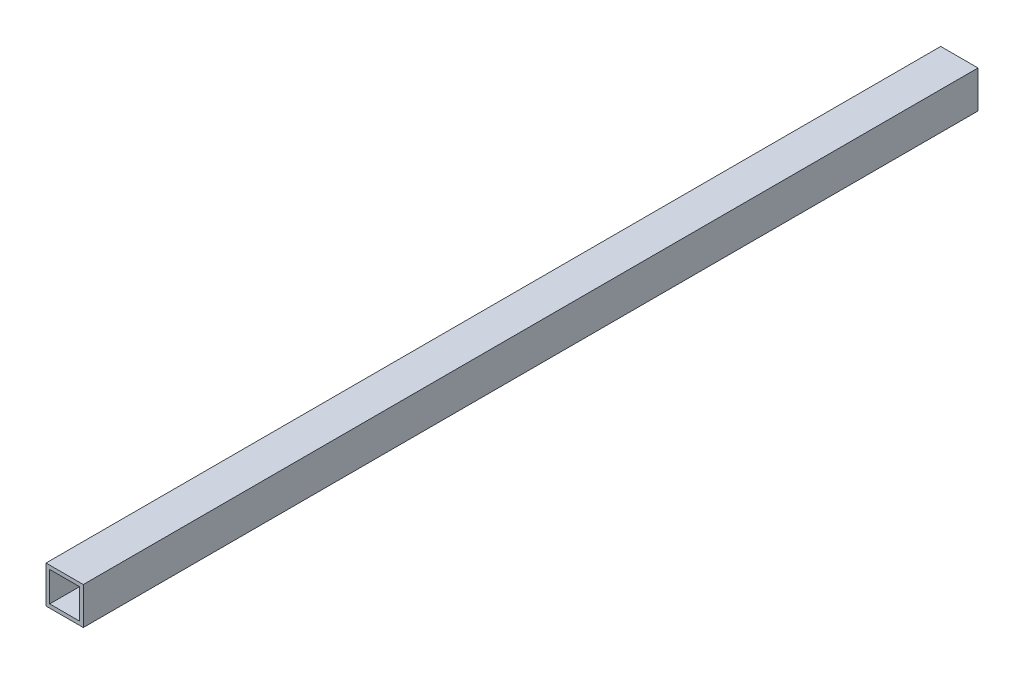
SolidWorks part; units mm, degrees
ref_plane "Płaszczyzna przednia" through (0, 0, 0) normal (0, 0, 1) x (1, 0, 0)
ref_plane "Płaszczyzna górna" through (0, 0, 0) normal (0, 1, 0) x (1, 0, 0)
ref_plane "Płaszczyzna prawa" through (0, 0, 0) normal (1, 0, 0) x (0, 0, -1)
sketch "Szkic1" plane through (0, 0, 0) normal (0, 0, 1) x (1, 0, 0)
  line L1 (-10, 10) -> (10, 10)
  line L2 (-10, 10) -> (-10, -10)
  line L3 (-10, -10) -> (10, -10)
  line L4 (10, 10) -> (10, -10)
  line L5 (-10, 10) -> (10, -10) construction
  line L6 (-10, -10) -> (10, 10) construction
  line L7 (-8, -8) -> (8, -8)
  line L8 (-8, -8) -> (-8, 8)
  line L9 (-8, 8) -> (8, 8)
  line L10 (8, -8) -> (8, 8)
  line L11 (-8, -8) -> (8, 8) construction
  line L12 (-8, 8) -> (8, -8) construction
  point P0 (0, 0)
  point P5 (0, 0)
  dimension "D1" = 20
  dimension "D2" = 16
extrude "Dodanie-wyciągnięcie1" add sketch "Szkic1" along normal blind 480
